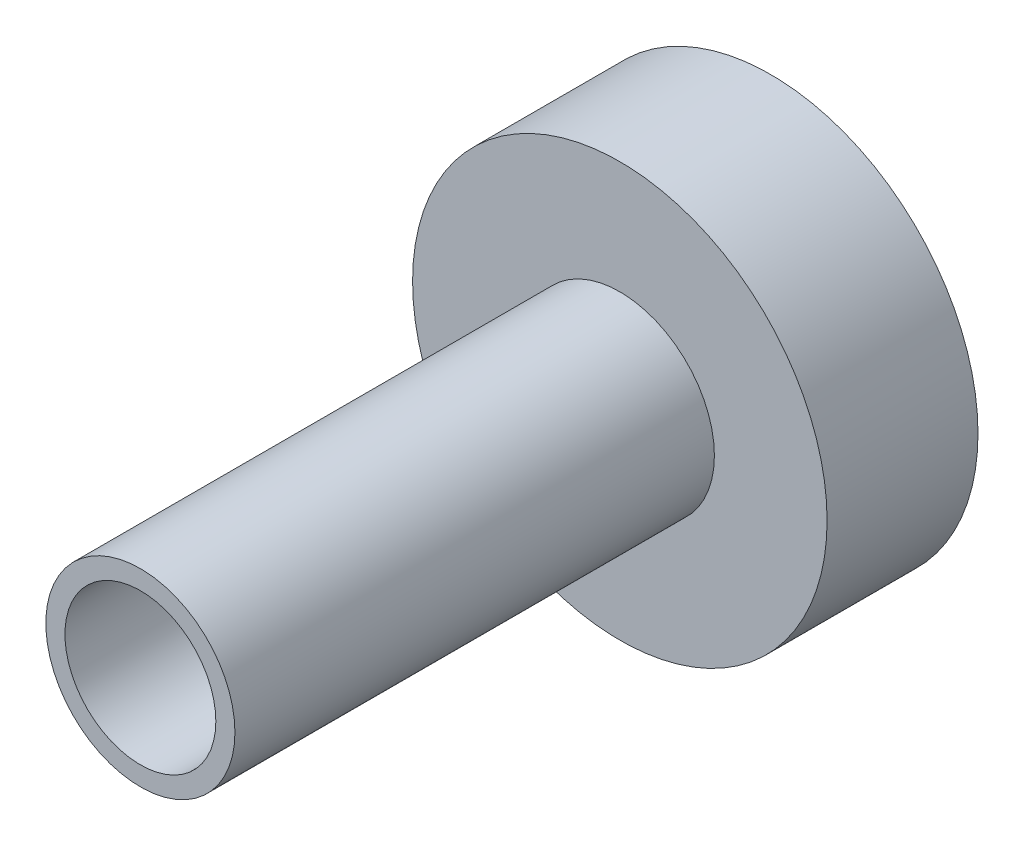
SolidWorks part; units mm, degrees
ref_plane "Front Plane" through (0, 0, 0) normal (0, 0, 1) x (1, 0, 0)
ref_plane "Top Plane" through (0, 0, 0) normal (0, 1, 0) x (1, 0, 0)
ref_plane "Right Plane" through (0, 0, 0) normal (1, 0, 0) x (0, 0, -1)
sketch "Sketch1" plane through (0, 0, 0) normal (0, 0, 1) x (1, 0, 0)
  circle A0 centre (0, 0) radius 10.85
  circle A1 centre (0, 0) radius 3.95
  dimension "D1" = 21.7
  dimension "D2" = 7.9
extrude "Boss-Extrude1" add sketch "Sketch1" along normal blind 33
sketch "Sketch2" plane through (0, 0, 33) normal (0, 0, 1) x (1, 0, 0)
  circle A0 centre (0, 0) radius 4.95
  circle A1 centre (0, 0) radius 10.85
  circle A2 centre (0, 0) radius 10.85 construction
  dimension "D1" = 9.9
extrude "Cut-Extrude1" cut sketch "Sketch2" against normal blind 25.1
